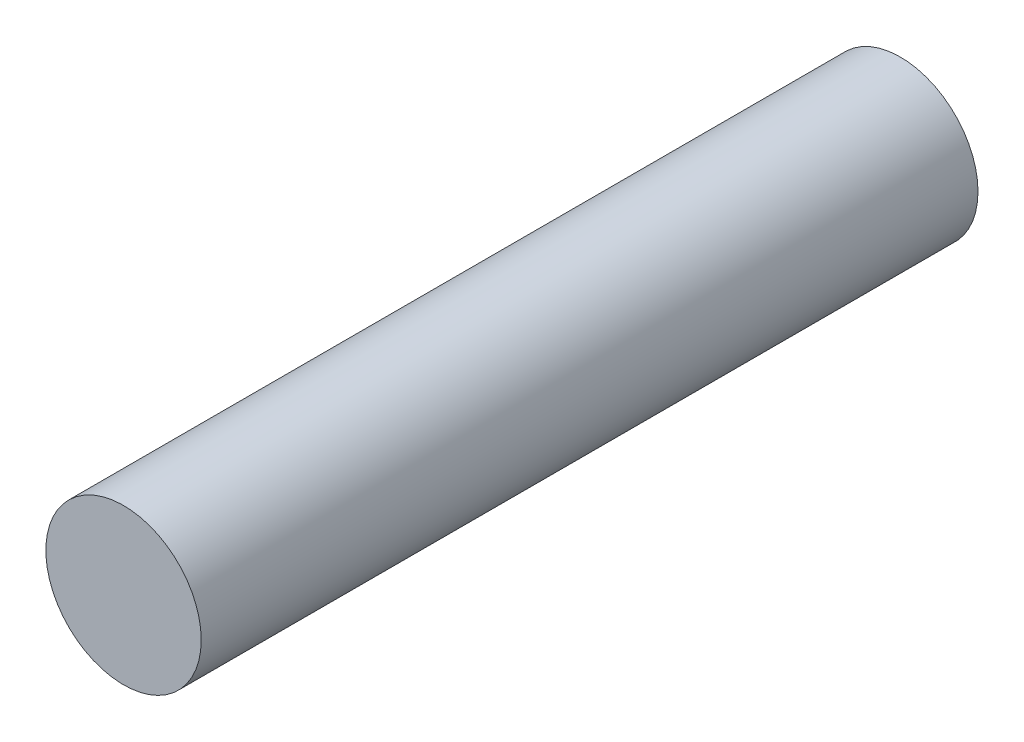
SolidWorks part; units mm, degrees
material "Cast Alloy Steel"
ref_plane "Front" through (0, 0, 0) normal (0, 0, 1) x (1, 0, 0)
ref_plane "Top" through (0, 0, 0) normal (0, 1, 0) x (1, 0, 0)
ref_plane "Right" through (0, 0, 0) normal (1, 0, 0) x (0, 0, -1)
sketch "Sketch1" plane through (0, 0, 0) normal (0, 0, 1) x (1, 0, 0)
  circle A0 centre (0, 0) radius 1
extrude "Boss-Extrude1" add sketch "Sketch1" along normal blind 10
